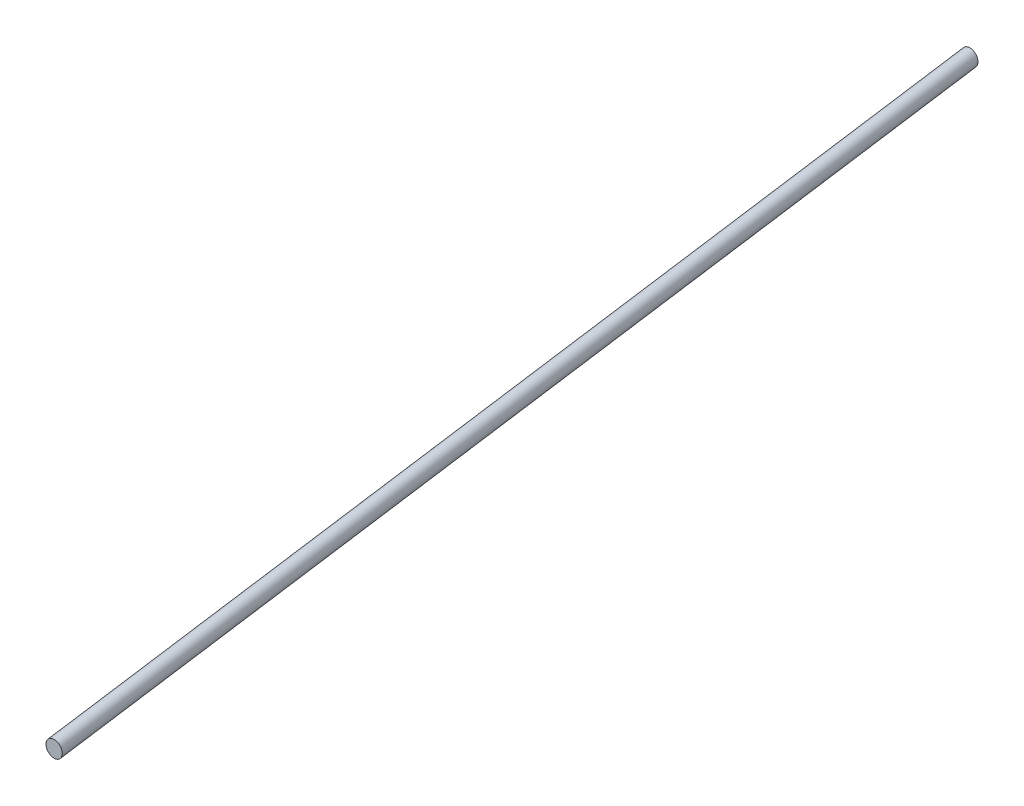
SolidWorks part; units mm, degrees
ref_plane "前视基准面" through (0, 0, 0) normal (0, 0, 1) x (1, 0, 0)
ref_plane "上视基准面" through (0, 0, 0) normal (0, 1, 0) x (1, 0, 0)
ref_plane "右视基准面" through (0, 0, 0) normal (1, 0, 0) x (0, 0, -1)
curve "曲线1"
  spline degree 3 poles (186.5, 0.1118, 0) (186.1892, 0.1855, 0) (185.5675, 0.3328, 0) (184.635, 0.5537, 0) (183.7026, 0.7744, 0) (182.7701, 0.9948, 0) (181.8376, 1.2145, 0) (180.9051, 1.4337, 0) (179.9726, 1.652, 0) (178.7297, 1.9419, 0) (177.1757, 2.3014, 0) (175.3109, 2.728, 0) (173.4457, 3.1494, 0) (171.5809, 3.5657, 0) (169.7157, 3.9772, 0) (167.8508, 4.3838, 0) (165.9856, 4.7859, 0) (164.1208, 5.1833, 0) (162.2556, 5.576, 0) (160.3908, 5.9638, 0) (158.5257, 6.3468, 0) (156.6608, 6.7247, 0) (154.7957, 7.0976, 0) (152.9308, 7.4653, 0) (151.0657, 7.8278, 0) (149.2008, 8.185, 0) (147.3357, 8.5369, 0) (145.4708, 8.8834, 0) (143.6056, 9.2245, 0) (141.7408, 9.5601, 0) (139.8756, 9.8903, 0) (138.0108, 10.2149, 0) (136.1456, 10.5341, 0) (134.2808, 10.8476, 0) (132.4156, 11.1557, 0) (130.5507, 11.4581, 0) (128.6856, 11.7549, 0) (126.8208, 12.0459, 0) (124.9556, 12.3308, 0) (123.0908, 12.6092, 0) (121.2257, 12.8811, 0) (119.3608, 13.146, 0) (117.4957, 13.4038, 0) (115.6308, 13.654, 0) (113.7657, 13.8966, 0) (111.9008, 14.1311, 0) (110.0357, 14.3574, 0) (108.1708, 14.5754, 0) (106.3056, 14.785, 0) (104.4407, 14.9862, 0) (102.5756, 15.1791, 0) (100.7107, 15.3636, 0) (98.8455, 15.5397, 0) (96.9806, 15.7073, 0) (95.1155, 15.8666, 0) (93.2506, 16.0175, 0) (91.3854, 16.1599, 0) (89.5205, 16.2936, 0) (87.6554, 16.4183, 0) (85.7905, 16.5335, 0) (83.9254, 16.6389, 0) (82.0604, 16.734, 0) (80.1953, 16.8187, 0) (78.3303, 16.8924, 0) (76.4652, 16.9548, 0) (74.6002, 17.0055, 0) (72.7351, 17.0439, 0) (70.8701, 17.0706, 0) (69.005, 17.0858, 0) (67.14, 17.0901, 0) (65.275, 17.0839, 0) (63.4099, 17.0678, 0) (61.5449, 17.0422, 0) (59.6799, 17.0076, 0) (57.8149, 16.9643, 0) (55.9498, 16.9131, 0) (54.0848, 16.8547, 0) (52.2196, 16.7871, 0) (50.3546, 16.7086, 0) (48.4893, 16.6167, 0) (46.6243, 16.5092, 0) (44.7588, 16.3837, 0) (42.8937, 16.238, 0) (41.028, 16.0697, 0) (39.163, 15.8765, 0) (37.2969, 15.6558, 0) (35.4322, 15.405, 0) (33.5661, 15.1238, 0) (31.7016, 14.8124, 0) (29.8355, 14.4709, 0) (27.971, 14.1006, 0) (26.1044, 13.6997, 0) (24.2398, 13.2683, 0) (22.3723, 12.8019, 0) (20.5078, 12.299, 0) (18.6397, 11.7536, 0) (16.7761, 11.1641, 0) (14.9067, 10.5272, 0) (13.0406, 9.8463, 0) (11.4871, 9.2257, 0) (10.251, 8.6897, 0) (9.3149, 8.2577, 0) (8.3827, 7.7965, 0) (7.4442, 7.2957, 0) (6.5109, 6.7553, 0) (5.5667, 6.1517, 0) (4.6345, 5.4819, 0) (3.7611, 4.7729, 0) (2.9674, 4.0489, 0) (2.3522, 3.4464, 0) (1.8596, 2.9514, 0) (1.4788, 2.552, 0) (1.1014, 2.1276, 0) (0.7887, 1.7312, 0) (0.5474, 1.381, 0) (0.3916, 1.1217, 0) (0.2725, 0.8921, 0) (0.1949, 0.7195, 0) (0.136, 0.5671, 0) (0.0831, 0.4095, 0) (0.0327, 0.2211, 0) (-0.0162, -0.071, 0) (-0.0149, -0.4421, 0) (0.0563, -0.7734, 0) (0.1356, -0.9912, 0) (0.1948, -1.1301, 0) (0.2723, -1.2864, 0) (0.3907, -1.4912, 0) (0.546, -1.7187, 0) (0.7851, -2.0147, 0) (1.0965, -2.3364, 0) (1.4716, -2.656, 0) (1.8524, -2.9339, 0) (2.3365, -3.2337, 0) (2.9612, -3.5284, 0) (3.7741, -3.807, 0) (4.6559, -4.0277, 0) (5.5923, -4.2156, 0) (6.5261, -4.402, 0) (7.4574, -4.5763, 0) (8.3903, -4.7294, 0) (9.3228, -4.8608, 0) (10.2562, -4.9705, 0) (11.4987, -5.092, 0) (13.0535, -5.2066, 0) (14.9192, -5.3092, 0) (16.7846, -5.4024, 0) (18.6495, -5.482, 0) (20.5147, -5.5442, 0) (22.3797, -5.5905, 0) (24.2449, -5.6228, 0) (26.1099, -5.6419, 0) (27.975, -5.6487, 0) (29.84, -5.6442, 0) (31.7051, -5.6295, 0) (33.5701, -5.6055, 0) (35.4351, -5.5733, 0) (37.3001, -5.5337, 0) (39.1651, -5.4878, 0) (41.0301, -5.4363, 0) (42.8951, -5.3798, 0) (44.7601, -5.3192, 0) (46.6251, -5.2551, 0) (48.4901, -5.1881, 0) (50.355, -5.1191, 0) (52.22, -5.0486, 0) (54.085, -4.9774, 0) (55.95, -4.9063, 0) (57.815, -4.8359, 0) (59.68, -4.7662, 0) (61.545, -4.6971, 0) (63.41, -4.6284, 0) (65.275, -4.5602, 0) (67.14, -4.4922, 0) (69.005, -4.4244, 0) (70.87, -4.3567, 0) (72.735, -4.2891, 0) (74.6, -4.2213, 0) (76.465, -4.1533, 0) (78.33, -4.0852, 0) (80.195, -4.0168, 0) (82.06, -3.9484, 0) (83.925, -3.8798, 0) (85.79, -3.8112, 0) (87.655, -3.7425, 0) (89.52, -3.6738, 0) (91.385, -3.6051, 0) (93.25, -3.5364, 0) (95.115, -3.4678, 0) (96.98, -3.3992, 0) (98.845, -3.3306, 0) (100.71, -3.2621, 0) (102.575, -3.1937, 0) (104.44, -3.1252, 0) (106.305, -3.0568, 0) (108.17, -2.9883, 0) (110.035, -2.9199, 0) (111.9, -2.8515, 0) (113.765, -2.783, 0) (115.63, -2.7145, 0) (117.495, -2.6461, 0) (119.36, -2.5776, 0) (121.225, -2.5091, 0) (123.09, -2.4406, 0) (124.955, -2.3721, 0) (126.82, -2.3035, 0) (128.685, -2.2351, 0) (130.55, -2.1665, 0) (132.415, -2.0981, 0) (134.28, -2.0295, 0) (136.145, -1.9611, 0) (138.01, -1.8926, 0) (139.875, -1.8241, 0) (141.74, -1.7556, 0) (143.605, -1.6871, 0) (145.47, -1.6186, 0) (147.335, -1.5501, 0) (149.2, -1.4816, 0) (151.065, -1.4131, 0) (152.93, -1.3446, 0) (154.795, -1.2761, 0) (156.66, -1.2076, 0) (158.525, -1.1392, 0) (160.39, -1.0707, 0) (162.255, -1.0022, 0) (164.12, -0.9337, 0) (165.985, -0.8652, 0) (167.85, -0.7967, 0) (169.715, -0.7282, 0) (171.58, -0.6597, 0) (173.445, -0.5912, 0) (175.31, -0.5227, 0) (177.175, -0.4542, 0) (178.7292, -0.3972, 0) (179.9725, -0.3515, 0) (180.905, -0.3173, 0) (181.8375, -0.283, 0) (182.77, -0.2488, 0) (183.7025, -0.2145, 0) (184.635, -0.1803, 0) (185.5675, -0.146, 0) (186.1892, -0.1232, 0) (186.5, -0.1118, 0) knots 0 0 0 0 0.002514 0.005028 0.007541 0.010055 0.012567 0.01508 0.017592 0.020104 0.025124 0.030144 0.035158 0.040172 0.04518 0.050189 0.055192 0.060195 0.065193 0.070191 0.075184 0.080177 0.085164 0.090152 0.095134 0.100117 0.105094 0.110071 0.115043 0.120015 0.124982 0.129949 0.134911 0.139873 0.14483 0.149787 0.154739 0.159692 0.164639 0.169587 0.174529 0.179472 0.184409 0.189346 0.194278 0.19921 0.204137 0.209064 0.213985 0.218907 0.223824 0.228741 0.233654 0.238567 0.243476 0.248385 0.25329 0.258196 0.263098 0.268 0.2729 0.277799 0.282695 0.287592 0.292486 0.29738 0.302273 0.307166 0.312058 0.316951 0.321843 0.326735 0.331628 0.33652 0.341414 0.346308 0.351203 0.356098 0.360995 0.365892 0.370794 0.375696 0.380605 0.385515 0.390437 0.39536 0.400301 0.405243 0.410209 0.415176 0.420172 0.425167 0.430199 0.435232 0.440314 0.445396 0.450545 0.455694 0.460935 0.466175 0.468856 0.471537 0.474288 0.477039 0.479906 0.482773 0.485854 0.488934 0.491619 0.494305 0.49571 0.497115 0.498647 0.500178 0.501085 0.501992 0.502556 0.503119 0.50348 0.503841 0.504427 0.505013 0.506168 0.507324 0.507658 0.507992 0.508511 0.50903 0.509853 0.510676 0.512022 0.513369 0.514549 0.515728 0.517845 0.519968 0.522481 0.524993 0.527484 0.529974 0.532448 0.534923 0.537383 0.539844 0.544747 0.54965 0.554547 0.559445 0.564339 0.569233 0.574126 0.579018 0.58391 0.588803 0.593695 0.598587 0.60348 0.608373 0.613267 0.618161 0.623055 0.62795 0.632845 0.63774 0.642636 0.647531 0.652427 0.657322 0.662218 0.667113 0.672009 0.676904 0.6818 0.686695 0.69159 0.696486 0.701381 0.706276 0.711172 0.716067 0.720962 0.725858 0.730753 0.735649 0.740544 0.745439 0.750335 0.75523 0.760126 0.765021 0.769916 0.774812 0.779707 0.784603 0.789498 0.794393 0.799289 0.804184 0.80908 0.813975 0.81887 0.823766 0.828661 0.833557 0.838452 0.843347 0.848243 0.853138 0.858034 0.862929 0.867824 0.87272 0.877615 0.882511 0.887406 0.892301 0.897197 0.902092 0.906987 0.911883 0.916778 0.921674 0.926569 0.931464 0.93636 0.941255 0.946151 0.951046 0.955941 0.960837 0.965732 0.970628 0.975523 0.980418 0.982866 0.985314 0.987762 0.990209 0.992657 0.995105 0.997552 1 1 1 1
sketch "草图1" plane through (0, 0, 0) normal (0, 0, 1) x (1, 0, 0)
  line L0 (186.5, 0.1118) -> (187.3165, -0.0818)
  line L1 (186.5, -0.1118) -> (187.3165, -0.0818)
  spline S0 degree 3 poles (1071.8943, 1773.6481) (478.7543, -73.3687) (332.3255, -34.4387) (184.635, 0.5537) (183.7026, 0.7744) (182.7701, 0.9948) (181.8376, 1.2145) (180.9051, 1.4337) (179.9726, 1.652) (178.7297, 1.9419) (177.1757, 2.3014) (175.3109, 2.728) (173.4457, 3.1494) (170.9597, 3.7043) (167.8519, 4.3859) (164.1219, 5.1854) (159.7716, 6.0959) (156.0406, 6.8521) (152.9308, 7.4653) (151.0657, 7.8278) (149.2008, 8.185) (147.3357, 8.5369) (145.4708, 8.8834) (143.6056, 9.2245) (141.7408, 9.5601) (139.2547, 10.0002) (136.7681, 10.4294) (134.2808, 10.8476) (132.4156, 11.1557) (130.5507, 11.4581) (128.6856, 11.7549) (126.8208, 12.0459) (124.9556, 12.3308) (123.0908, 12.6092) (121.2257, 12.8811) (119.3608, 13.146) (117.4957, 13.4038) (115.0097, 13.7374) (112.523, 14.0557) (109.4148, 14.4328) (106.9281, 14.7178) (104.4407, 14.9862) (102.5756, 15.1791) (100.7107, 15.3636) (98.8455, 15.5397) (96.3593, 15.7632) (93.2513, 16.0216) (90.1425, 16.252) (87.6554, 16.4183) (85.7905, 16.5335) (83.9254, 16.6389) (82.0604, 16.734) (80.1953, 16.8187) (78.3303, 16.8924) (76.4652, 16.9548) (73.9787, 17.0223) (71.4919, 17.0655) (69.005, 17.0858) (67.14, 17.0901) (65.275, 17.0839) (63.4099, 17.0678) (61.5449, 17.0422) (59.6799, 17.0076) (57.8149, 16.9643) (55.9498, 16.9131) (54.0848, 16.8547) (52.2196, 16.7871) (50.3546, 16.7086) (48.4893, 16.6167) (46.6243, 16.5092) (44.7588, 16.3837) (42.8937, 16.238) (41.028, 16.0697) (39.163, 15.8765) (37.2969, 15.6558) (35.4322, 15.405) (33.5661, 15.1238) (31.7016, 14.8124) (29.8355, 14.4709) (27.971, 14.1006) (26.1044, 13.6997) (24.2398, 13.2683) (22.3723, 12.8019) (20.5078, 12.299) (18.6397, 11.7536) (16.7761, 11.1641) (14.9067, 10.5272) (13.0406, 9.8463) (11.4871, 9.2257) (10.251, 8.6897) (9.3149, 8.2577) (8.3827, 7.7965) (7.4442, 7.2957) (6.5109, 6.7553) (5.5667, 6.1517) (4.6345, 5.4819) (3.7611, 4.7729) (2.9674, 4.0489) (2.3522, 3.4464) (1.8596, 2.9514) (1.4788, 2.552) (1.1014, 2.1276) (0.7887, 1.7312) (0.5474, 1.381) (0.3916, 1.1217) (0.2725, 0.8921) (0.1949, 0.7195) (0.136, 0.5671) (0.0831, 0.4095) (0.0327, 0.2211) (-0.0162, -0.071) (-0.0149, -0.4421) (0.0563, -0.7734) (0.1356, -0.9912) (0.1948, -1.1301) (0.2723, -1.2864) (0.3907, -1.4912) (0.546, -1.7187) (0.7851, -2.0147) (1.0965, -2.3364) (1.4716, -2.656) (1.8524, -2.9339) (2.3365, -3.2337) (2.9612, -3.5284) (3.7741, -3.807) (4.6559, -4.0277) (5.5923, -4.2156) (6.5261, -4.402) (7.4574, -4.5763) (8.3903, -4.7294) (9.3228, -4.8608) (10.2562, -4.9705) (11.4987, -5.092) (13.0535, -5.2066) (14.9192, -5.3092) (16.7846, -5.4024) (18.6495, -5.482) (20.5147, -5.5442) (22.3797, -5.5905) (24.8665, -5.6336) (27.3533, -5.6502) (29.84, -5.6442) (32.3268, -5.6246) (34.8135, -5.5864) (37.3001, -5.5337) (39.1651, -5.4878) (42.2737, -5.4019) (45.3819, -5.2997) (49.1118, -5.1658) (51.5984, -5.0723) (54.085, -4.9774) (57.1933, -4.8589) (61.5449, -4.6964) (66.5183, -4.5147) (70.2483, -4.3793) (73.3567, -4.2665) (75.8433, -4.176) (78.33, -4.0852) (80.195, -4.0168) (82.06, -3.9484) (83.925, -3.8798) (85.79, -3.8112) (87.655, -3.7425) (89.52, -3.6738) (91.385, -3.6051) (93.25, -3.5364) (95.7367, -3.4449) (98.2233, -3.3535) (100.71, -3.2621) (102.575, -3.1937) (104.44, -3.1252) (106.305, -3.0568) (108.7917, -2.9655) (111.2783, -2.8743) (113.765, -2.783) (116.8733, -2.6689) (119.9817, -2.5547) (123.09, -2.4406) (124.955, -2.3721) (126.82, -2.3035) (129.3067, -2.2122) (131.7933, -2.1209) (134.28, -2.0295) (136.145, -1.9611) (138.01, -1.8926) (140.4967, -1.8012) (142.9833, -1.7099) (145.47, -1.6186) (147.335, -1.5501) (149.8217, -1.4588) (152.3083, -1.3675) (154.795, -1.2761) (156.66, -1.2076) (158.525, -1.1392) (160.39, -1.0707) (162.255, -1.0022) (164.12, -0.9337) (166.6067, -0.8424) (169.0933, -0.751) (171.58, -0.6597) (174.0667, -0.5684) (176.5533, -0.4771) (179.04, -0.3857) (180.5942, -0.3287) (182.1483, -0.2716) (183.3917, -0.2259) (184.635, -0.1803) (849.3977, 24.2359) (1513.8472, 48.7041) (2182.9555, -62.1484) knots -1.186859 -1.186859 -1.186859 -1.186859 0.002514 0.005028 0.007541 0.010055 0.012567 0.01508 0.017592 0.020104 0.025124 0.030144 0.035158 0.040172 0.050189 0.060195 0.070191 0.085164 0.090152 0.095134 0.100117 0.105094 0.110071 0.115043 0.120015 0.124982 0.134911 0.139873 0.14483 0.149787 0.154739 0.159692 0.164639 0.169587 0.174529 0.179472 0.184409 0.189346 0.19921 0.204137 0.213985 0.218907 0.223824 0.228741 0.233654 0.238567 0.248385 0.258196 0.263098 0.268 0.2729 0.277799 0.282695 0.287592 0.292486 0.29738 0.307166 0.312058 0.316951 0.321843 0.326735 0.331628 0.33652 0.341414 0.346308 0.351203 0.356098 0.360995 0.365892 0.370794 0.375696 0.380605 0.385515 0.390437 0.39536 0.400301 0.405243 0.410209 0.415176 0.420172 0.425167 0.430199 0.435232 0.440314 0.445396 0.450545 0.455694 0.460935 0.466175 0.468856 0.471537 0.474288 0.477039 0.479906 0.482773 0.485854 0.488934 0.491619 0.494305 0.49571 0.497115 0.498647 0.500178 0.501085 0.501992 0.502556 0.503119 0.50348 0.503841 0.504427 0.505013 0.506168 0.507324 0.507658 0.507992 0.508511 0.50903 0.509853 0.510676 0.512022 0.513369 0.514549 0.515728 0.517845 0.519968 0.522481 0.524993 0.527484 0.529974 0.532448 0.534923 0.537383 0.539844 0.544747 0.54965 0.554547 0.559445 0.564339 0.569233 0.574126 0.58391 0.588803 0.593695 0.60348 0.608373 0.613267 0.618161 0.632845 0.63774 0.647531 0.652427 0.657322 0.672009 0.686695 0.696486 0.701381 0.711172 0.716067 0.720962 0.725858 0.730753 0.735649 0.740544 0.745439 0.750335 0.75523 0.760126 0.769916 0.774812 0.779707 0.784603 0.789498 0.794393 0.804184 0.80908 0.813975 0.828661 0.833557 0.838452 0.843347 0.848243 0.858034 0.862929 0.867824 0.87272 0.877615 0.887406 0.892301 0.897197 0.902092 0.911883 0.916778 0.921674 0.926569 0.931464 0.93636 0.941255 0.946151 0.955941 0.960837 0.965732 0.975523 0.980418 0.985314 0.987762 0.992657 0.995105 0.997552 6.227418 6.227418 6.227418 6.227418 only from (186.5, 0.1118) to (186.5, -0.1118) construction
  spline S1 degree 3 poles (186.5, 0.1118) (185.8783, 0.2591) (184.9459, 0.4802) (183.7026, 0.7744) (182.7701, 0.9948) (181.8376, 1.2145) (180.9051, 1.4337) (179.9726, 1.652) (178.7297, 1.9419) (177.1757, 2.3014) (175.3109, 2.728) (173.4457, 3.1494) (170.9597, 3.7043) (167.8519, 4.3859) (164.1219, 5.1854) (159.7716, 6.0959) (156.0406, 6.8521) (152.9308, 7.4653) (151.0657, 7.8278) (149.2008, 8.185) (147.3357, 8.5369) (145.4708, 8.8834) (143.6056, 9.2245) (141.7408, 9.5601) (139.2547, 10.0002) (136.7681, 10.4294) (134.2808, 10.8476) (132.4156, 11.1557) (130.5507, 11.4581) (128.6856, 11.7549) (126.8208, 12.0459) (124.9556, 12.3308) (123.0908, 12.6092) (121.2257, 12.8811) (119.3608, 13.146) (117.4957, 13.4038) (115.0097, 13.7374) (112.523, 14.0557) (109.4148, 14.4328) (106.9281, 14.7178) (104.4407, 14.9862) (102.5756, 15.1791) (100.7107, 15.3636) (98.8455, 15.5397) (96.3593, 15.7632) (93.2513, 16.0216) (90.1425, 16.252) (87.6554, 16.4183) (85.7905, 16.5335) (83.9254, 16.6389) (82.0604, 16.734) (80.1953, 16.8187) (78.3303, 16.8924) (76.4652, 16.9548) (73.9787, 17.0223) (71.4919, 17.0655) (69.005, 17.0858) (67.14, 17.0901) (65.275, 17.0839) (63.4099, 17.0678) (61.5449, 17.0422) (59.6799, 17.0076) (57.8149, 16.9643) (55.9498, 16.9131) (54.0848, 16.8547) (52.2196, 16.7871) (50.3546, 16.7086) (48.4893, 16.6167) (46.6243, 16.5092) (44.7588, 16.3837) (42.8937, 16.238) (41.028, 16.0697) (39.163, 15.8765) (37.2969, 15.6558) (35.4322, 15.405) (33.5661, 15.1238) (31.7016, 14.8124) (29.8355, 14.4709) (27.971, 14.1006) (26.1044, 13.6997) (24.2398, 13.2683) (22.3723, 12.8019) (20.5078, 12.299) (18.6397, 11.7536) (16.7761, 11.1641) (14.9067, 10.5272) (13.0406, 9.8463) (11.4871, 9.2257) (10.251, 8.6897) (9.3149, 8.2577) (8.3827, 7.7965) (7.4442, 7.2957) (6.5109, 6.7553) (5.5667, 6.1517) (4.6345, 5.4819) (3.7611, 4.7729) (2.9674, 4.0489) (2.3522, 3.4464) (1.8596, 2.9514) (1.4788, 2.552) (1.1014, 2.1276) (0.7887, 1.7312) (0.5474, 1.381) (0.3916, 1.1217) (0.2725, 0.8921) (0.1949, 0.7195) (0.136, 0.5671) (0.0831, 0.4095) (0.0327, 0.2211) (-0.0162, -0.071) (-0.0149, -0.4421) (0.0563, -0.7734) (0.1356, -0.9912) (0.1948, -1.1301) (0.2723, -1.2864) (0.3907, -1.4912) (0.546, -1.7187) (0.7851, -2.0147) (1.0965, -2.3364) (1.4716, -2.656) (1.8524, -2.9339) (2.3365, -3.2337) (2.9612, -3.5284) (3.7741, -3.807) (4.6559, -4.0277) (5.5923, -4.2156) (6.5261, -4.402) (7.4574, -4.5763) (8.3903, -4.7294) (9.3228, -4.8608) (10.2562, -4.9705) (11.4987, -5.092) (13.0535, -5.2066) (14.9192, -5.3092) (16.7846, -5.4024) (18.6495, -5.482) (20.5147, -5.5442) (22.3797, -5.5905) (24.8665, -5.6336) (27.3533, -5.6502) (29.84, -5.6442) (32.3268, -5.6246) (34.8135, -5.5864) (37.3001, -5.5337) (39.1651, -5.4878) (42.2737, -5.4019) (45.3819, -5.2997) (49.1118, -5.1658) (51.5984, -5.0723) (54.085, -4.9774) (57.1933, -4.8589) (61.5449, -4.6964) (66.5183, -4.5147) (70.2483, -4.3793) (73.3567, -4.2665) (75.8433, -4.176) (78.33, -4.0852) (80.195, -4.0168) (82.06, -3.9484) (83.925, -3.8798) (85.79, -3.8112) (87.655, -3.7425) (89.52, -3.6738) (91.385, -3.6051) (93.25, -3.5364) (95.7367, -3.4449) (98.2233, -3.3535) (100.71, -3.2621) (102.575, -3.1937) (104.44, -3.1252) (106.305, -3.0568) (108.7917, -2.9655) (111.2783, -2.8743) (113.765, -2.783) (116.8733, -2.6689) (119.9817, -2.5547) (123.09, -2.4406) (124.955, -2.3721) (126.82, -2.3035) (129.3067, -2.2122) (131.7933, -2.1209) (134.28, -2.0295) (136.145, -1.9611) (138.01, -1.8926) (140.4967, -1.8012) (142.9833, -1.7099) (145.47, -1.6186) (147.335, -1.5501) (149.8217, -1.4588) (152.3083, -1.3675) (154.795, -1.2761) (156.66, -1.2076) (158.525, -1.1392) (160.39, -1.0707) (162.255, -1.0022) (164.12, -0.9337) (166.6067, -0.8424) (169.0933, -0.751) (171.58, -0.6597) (174.0667, -0.5684) (176.5533, -0.4771) (179.04, -0.3857) (180.5942, -0.3287) (182.1483, -0.2716) (184.0133, -0.2031) (185.5675, -0.146) (186.5, -0.1118) knots 0 0 0 0 0.005028 0.007541 0.010055 0.012567 0.01508 0.017592 0.020104 0.025124 0.030144 0.035158 0.040172 0.050189 0.060195 0.070191 0.085164 0.090152 0.095134 0.100117 0.105094 0.110071 0.115043 0.120015 0.124982 0.134911 0.139873 0.14483 0.149787 0.154739 0.159692 0.164639 0.169587 0.174529 0.179472 0.184409 0.189346 0.19921 0.204137 0.213985 0.218907 0.223824 0.228741 0.233654 0.238567 0.248385 0.258196 0.263098 0.268 0.2729 0.277799 0.282695 0.287592 0.292486 0.29738 0.307166 0.312058 0.316951 0.321843 0.326735 0.331628 0.33652 0.341414 0.346308 0.351203 0.356098 0.360995 0.365892 0.370794 0.375696 0.380605 0.385515 0.390437 0.39536 0.400301 0.405243 0.410209 0.415176 0.420172 0.425167 0.430199 0.435232 0.440314 0.445396 0.450545 0.455694 0.460935 0.466175 0.468856 0.471537 0.474288 0.477039 0.479906 0.482773 0.485854 0.488934 0.491619 0.494305 0.49571 0.497115 0.498647 0.500178 0.501085 0.501992 0.502556 0.503119 0.50348 0.503841 0.504427 0.505013 0.506168 0.507324 0.507658 0.507992 0.508511 0.50903 0.509853 0.510676 0.512022 0.513369 0.514549 0.515728 0.517845 0.519968 0.522481 0.524993 0.527484 0.529974 0.532448 0.534923 0.537383 0.539844 0.544747 0.54965 0.554547 0.559445 0.564339 0.569233 0.574126 0.58391 0.588803 0.593695 0.60348 0.608373 0.613267 0.618161 0.632845 0.63774 0.647531 0.652427 0.657322 0.672009 0.686695 0.696486 0.701381 0.711172 0.716067 0.720962 0.725858 0.730753 0.735649 0.740544 0.745439 0.750335 0.75523 0.760126 0.769916 0.774812 0.779707 0.784603 0.789498 0.794393 0.804184 0.80908 0.813975 0.828661 0.833557 0.838452 0.843347 0.848243 0.858034 0.862929 0.867824 0.87272 0.877615 0.887406 0.892301 0.897197 0.902092 0.911883 0.916778 0.921674 0.926569 0.931464 0.93636 0.941255 0.946151 0.955941 0.960837 0.965732 0.975523 0.980418 0.985314 0.987762 0.992657 1 1 1 1
curve "组合曲线1"
ref_plane "基准面4" through (0, 0, 519) normal (0, 0, 1) x (1, 0, 0)
sketch "草图2" plane through (0, 0, 519) normal (0, 0, 1) x (1, 0, 0)
  line L2 (187.3165, -0.0818) -> (186.8021, 0.0402)
  line L3 (186.8021, -0.1007) -> (187.3165, -0.0818)
  spline S1 degree 3 poles (186.8021, 0.0402) (186.2146, 0.1794) (185.4313, 0.3651) (184.4521, 0.5965) (183.8645, 0.735) (183.2771, 0.873) (182.6895, 1.0106) (181.9064, 1.1932) (180.9273, 1.4197) (179.7524, 1.6885) (178.5773, 1.954) (177.011, 2.3036) (175.0529, 2.733) (172.7029, 3.2368) (169.962, 3.8104) (167.6113, 4.2869) (165.652, 4.6732) (164.0857, 4.9777) (162.519, 5.2755) (160.9518, 5.5667) (159.7767, 5.7816) (158.6017, 5.993) (157.0354, 6.2703) (155.4687, 6.5408) (153.9016, 6.8042) (152.7265, 6.9983) (151.5515, 7.1888) (150.3764, 7.3759) (149.2015, 7.5592) (148.0263, 7.7387) (146.8514, 7.9141) (145.2851, 8.1425) (143.7184, 8.3621) (141.7599, 8.6249) (140.1932, 8.8254) (138.2349, 9.063) (136.6682, 9.2426) (135.101, 9.4117) (133.9259, 9.5333) (132.7509, 9.6495) (131.5758, 9.7604) (130.0094, 9.9013) (128.0512, 10.0641) (126.0925, 10.2092) (124.5255, 10.314) (123.3505, 10.3866) (122.1754, 10.453) (121.0004, 10.5129) (119.8253, 10.5663) (118.6503, 10.6127) (117.4752, 10.652) (115.9086, 10.6946) (114.3418, 10.7218) (112.775, 10.7346) (111.5999, 10.7373) (110.4248, 10.7334) (109.2498, 10.7232) (108.0747, 10.7071) (106.8997, 10.6853) (105.7246, 10.658) (104.5496, 10.6257) (103.3745, 10.5889) (102.1994, 10.5464) (101.0243, 10.4969) (99.8491, 10.439) (98.6741, 10.3713) (97.4987, 10.2922) (96.3237, 10.2004) (95.1481, 10.0944) (93.9731, 9.9727) (92.7974, 9.8336) (91.6225, 9.6756) (90.4468, 9.4984) (89.2721, 9.3022) (88.0964, 9.0871) (86.9217, 8.8538) (85.7456, 8.6012) (84.5708, 8.3294) (83.3943, 8.0355) (82.2195, 7.7187) (81.0425, 7.375) (79.8683, 7.0036) (78.6906, 6.6023) (77.5148, 6.1733) (76.5361, 5.7823) (75.7573, 5.4447) (75.1675, 5.1725) (74.5801, 4.8819) (73.9888, 4.5664) (73.4008, 4.2259) (72.806, 3.8456) (72.2186, 3.4236) (71.6683, 2.9769) (71.1683, 2.5208) (70.7807, 2.1411) (70.4703, 1.8292) (70.2304, 1.5776) (69.9926, 1.3102) (69.7956, 1.0605) (69.6436, 0.8398) (69.5454, 0.6765) (69.4703, 0.5318) (69.4215, 0.4231) (69.3844, 0.327) (69.3511, 0.2278) (69.3193, 0.1091) (69.2885, -0.075) (69.2893, -0.3088) (69.3342, -0.5175) (69.3841, -0.6548) (69.4214, -0.7423) (69.4702, -0.8408) (69.5448, -0.9698) (69.6427, -1.1131) (69.7933, -1.2996) (69.9895, -1.5023) (70.2258, -1.7037) (70.4657, -1.8787) (70.7708, -2.0676) (71.1644, -2.2533) (71.6765, -2.4288) (72.2321, -2.5679) (72.8221, -2.6862) (73.4104, -2.8037) (73.9972, -2.9135) (74.585, -3.01) (75.1724, -3.0928) (75.7605, -3.1619) (76.5434, -3.2385) (77.5229, -3.3106) (78.6984, -3.3753) (79.8737, -3.434) (81.0487, -3.4842) (82.2238, -3.5233) (83.3989, -3.5525) (84.9657, -3.5796) (86.5325, -3.5901) (88.0992, -3.5863) (89.666, -3.574) (91.2328, -3.55) (92.7994, -3.5167) (93.9744, -3.4878) (95.933, -3.4337) (97.8913, -3.3693) (100.2413, -3.2849) (102.1997, -3.2113) (104.9413, -3.1062) (108.0747, -2.9892) (111.2082, -2.8747) (113.5583, -2.7894) (115.5167, -2.7184) (117.0834, -2.6614) (118.6501, -2.6041) (119.8251, -2.561) (121.0002, -2.5179) (122.1752, -2.4747) (123.7419, -2.4171) (125.3086, -2.3593) (126.8753, -2.3016) (128.0504, -2.2583) (129.6171, -2.2007) (131.1838, -2.1431) (132.7505, -2.0856) (133.9255, -2.0424) (135.1006, -1.9993) (136.2756, -1.9562) (137.8423, -1.8987) (139.409, -1.8412) (140.9757, -1.7837) (142.9341, -1.7118) (144.8925, -1.6398) (147.2426, -1.5536) (148.8093, -1.496) (150.7677, -1.4241) (152.3344, -1.3665) (153.9011, -1.309) (155.0761, -1.2658) (156.2512, -1.2227) (157.8179, -1.1651) (159.3846, -1.1076) (160.9513, -1.05) (162.1264, -1.0069) (163.6931, -0.9494) (165.2598, -0.8918) (166.8265, -0.8343) (168.7849, -0.7623) (170.7433, -0.6904) (172.7017, -0.6185) (174.2684, -0.561) (175.8351, -0.5034) (177.4018, -0.4459) (178.9685, -0.3884) (180.5352, -0.3308) (182.1019, -0.2733) (183.0811, -0.2373) (184.0603, -0.2014) (185.2354, -0.1582) (186.2145, -0.1223) (186.8021, -0.1007) knots 0 0 0 0 0.007541 0.010055 0.012567 0.01508 0.017592 0.020104 0.025124 0.030144 0.035158 0.040172 0.050189 0.060195 0.070191 0.085164 0.090152 0.095134 0.105094 0.110071 0.115043 0.120015 0.124982 0.134911 0.139873 0.14483 0.149787 0.154739 0.159692 0.164639 0.169587 0.174529 0.184409 0.189346 0.19921 0.204137 0.213985 0.218907 0.223824 0.228741 0.233654 0.238567 0.248385 0.258196 0.263098 0.268 0.2729 0.277799 0.282695 0.287592 0.292486 0.29738 0.307166 0.312058 0.316951 0.321843 0.326735 0.331628 0.33652 0.341414 0.346308 0.351203 0.356098 0.360995 0.365892 0.370794 0.375696 0.380605 0.385515 0.390437 0.39536 0.400301 0.405243 0.410209 0.415176 0.420172 0.425167 0.430199 0.435232 0.440314 0.445396 0.450545 0.455694 0.460935 0.466175 0.468856 0.471537 0.474288 0.477039 0.479906 0.482773 0.485854 0.488934 0.491619 0.494305 0.49571 0.497115 0.498647 0.500178 0.501085 0.501992 0.502556 0.503119 0.50348 0.503841 0.504427 0.505013 0.506168 0.507324 0.507658 0.507992 0.508511 0.50903 0.509853 0.510676 0.512022 0.513369 0.514549 0.515728 0.517845 0.519968 0.522481 0.524993 0.527484 0.529974 0.532448 0.534923 0.537383 0.539844 0.544747 0.54965 0.554547 0.559445 0.564339 0.569233 0.574126 0.58391 0.588803 0.593695 0.60348 0.608373 0.613267 0.618161 0.632845 0.63774 0.647531 0.657322 0.672009 0.686695 0.696486 0.701381 0.711172 0.716067 0.720962 0.725858 0.730753 0.735649 0.745439 0.750335 0.75523 0.760126 0.769916 0.774812 0.779707 0.784603 0.789498 0.794393 0.804184 0.80908 0.813975 0.828661 0.833557 0.843347 0.848243 0.858034 0.862929 0.867824 0.87272 0.877615 0.887406 0.892301 0.897197 0.902092 0.911883 0.916778 0.921674 0.93636 0.941255 0.946151 0.955941 0.960837 0.965732 0.975523 0.980418 0.985314 0.987762 0.992657 1 1 1 1
curve "组合曲线2"
sketch3d "3D草图1"
  line L0 (-0.0101, -0.1358, 0) -> (69.2923, -0.1173, 519)
  line L1 (187.3165, -0.0818, 0) -> (187.3165, -0.0818, 519)
  line L2 (187.3165, -0.0818, 0) -> (186.5, 0.1118, 0) construction
  line L3 (186.5, -0.1118, 0) -> (187.3165, -0.0818, 0) construction
  line L4 (187.3165, -0.0818, 519) -> (186.8021, 0.0402, 519) construction
  line L5 (186.8021, -0.1007, 519) -> (187.3165, -0.0818, 519) construction
  spline S0 degree 3 poles (186.5, 0.1118, 0) (185.8783, 0.2591, 0) (184.9459, 0.4802, 0) (183.7026, 0.7744, 0) (182.7701, 0.9948, 0) (181.8376, 1.2145, 0) (180.9051, 1.4337, 0) (179.9726, 1.652, 0) (178.7297, 1.9419, 0) (177.1757, 2.3014, 0) (175.3109, 2.728, 0) (173.4457, 3.1494, 0) (170.9597, 3.7043, 0) (167.8519, 4.3859, 0) (164.1219, 5.1854, 0) (159.7716, 6.0959, 0) (156.0406, 6.8521, 0) (152.9308, 7.4653, 0) (151.0657, 7.8278, 0) (149.2008, 8.185, 0) (147.3357, 8.5369, 0) (145.4708, 8.8834, 0) (143.6056, 9.2245, 0) (141.7408, 9.5601, 0) (139.2547, 10.0002, 0) (136.7681, 10.4294, 0) (134.2808, 10.8476, 0) (132.4156, 11.1557, 0) (130.5507, 11.4581, 0) (128.6856, 11.7549, 0) (126.8208, 12.0459, 0) (124.9556, 12.3308, 0) (123.0908, 12.6092, 0) (121.2257, 12.8811, 0) (119.3608, 13.146, 0) (117.4957, 13.4038, 0) (115.0097, 13.7374, 0) (112.523, 14.0557, 0) (109.4148, 14.4328, 0) (106.9281, 14.7178, 0) (104.4407, 14.9862, 0) (102.5756, 15.1791, 0) (100.7107, 15.3636, 0) (98.8455, 15.5397, 0) (96.3593, 15.7632, 0) (93.2513, 16.0216, 0) (90.1425, 16.252, 0) (87.6554, 16.4183, 0) (85.7905, 16.5335, 0) (83.9254, 16.6389, 0) (82.0604, 16.734, 0) (80.1953, 16.8187, 0) (78.3303, 16.8924, 0) (76.4652, 16.9548, 0) (73.9787, 17.0223, 0) (71.4919, 17.0655, 0) (69.005, 17.0858, 0) (67.14, 17.0901, 0) (65.275, 17.0839, 0) (63.4099, 17.0678, 0) (61.5449, 17.0422, 0) (59.6799, 17.0076, 0) (57.8149, 16.9643, 0) (55.9498, 16.9131, 0) (54.0848, 16.8547, 0) (52.2196, 16.7871, 0) (50.3546, 16.7086, 0) (48.4893, 16.6167, 0) (46.6243, 16.5092, 0) (44.7588, 16.3837, 0) (42.8937, 16.238, 0) (41.028, 16.0697, 0) (39.163, 15.8765, 0) (37.2969, 15.6558, 0) (35.4322, 15.405, 0) (33.5661, 15.1238, 0) (31.7016, 14.8124, 0) (29.8355, 14.4709, 0) (27.971, 14.1006, 0) (26.1044, 13.6997, 0) (24.2398, 13.2683, 0) (22.3723, 12.8019, 0) (20.5078, 12.299, 0) (18.6397, 11.7536, 0) (16.7761, 11.1641, 0) (14.9067, 10.5272, 0) (13.0406, 9.8463, 0) (11.4871, 9.2257, 0) (10.251, 8.6897, 0) (9.3149, 8.2577, 0) (8.3827, 7.7965, 0) (7.4442, 7.2957, 0) (6.5109, 6.7553, 0) (5.5667, 6.1517, 0) (4.6345, 5.4819, 0) (3.7611, 4.7729, 0) (2.9674, 4.0489, 0) (2.3522, 3.4464, 0) (1.8596, 2.9514, 0) (1.4788, 2.552, 0) (1.1014, 2.1276, 0) (0.7887, 1.7312, 0) (0.5474, 1.381, 0) (0.3916, 1.1217, 0) (0.2725, 0.8921, 0) (0.1949, 0.7195, 0) (0.136, 0.5671, 0) (0.0831, 0.4095, 0) (0.0327, 0.2211, 0) (-0.0162, -0.071, 0) (-0.0149, -0.4421, 0) (0.0563, -0.7734, 0) (0.1356, -0.9912, 0) (0.1948, -1.1301, 0) (0.2723, -1.2864, 0) (0.3907, -1.4912, 0) (0.546, -1.7187, 0) (0.7851, -2.0147, 0) (1.0965, -2.3364, 0) (1.4716, -2.656, 0) (1.8524, -2.9339, 0) (2.3365, -3.2337, 0) (2.9612, -3.5284, 0) (3.7741, -3.807, 0) (4.6559, -4.0277, 0) (5.5923, -4.2156, 0) (6.5261, -4.402, 0) (7.4574, -4.5763, 0) (8.3903, -4.7294, 0) (9.3228, -4.8608, 0) (10.2562, -4.9705, 0) (11.4987, -5.092, 0) (13.0535, -5.2066, 0) (14.9192, -5.3092, 0) (16.7846, -5.4024, 0) (18.6495, -5.482, 0) (20.5147, -5.5442, 0) (22.3797, -5.5905, 0) (24.8665, -5.6336, 0) (27.3533, -5.6502, 0) (29.84, -5.6442, 0) (32.3268, -5.6246, 0) (34.8135, -5.5864, 0) (37.3001, -5.5337, 0) (39.1651, -5.4878, 0) (42.2737, -5.4019, 0) (45.3819, -5.2997, 0) (49.1118, -5.1658, 0) (51.5984, -5.0723, 0) (54.085, -4.9774, 0) (57.1933, -4.8589, 0) (61.5449, -4.6964, 0) (66.5183, -4.5147, 0) (70.2483, -4.3793, 0) (73.3567, -4.2665, 0) (75.8433, -4.176, 0) (78.33, -4.0852, 0) (80.195, -4.0168, 0) (82.06, -3.9484, 0) (83.925, -3.8798, 0) (85.79, -3.8112, 0) (87.655, -3.7425, 0) (89.52, -3.6738, 0) (91.385, -3.6051, 0) (93.25, -3.5364, 0) (95.7367, -3.4449, 0) (98.2233, -3.3535, 0) (100.71, -3.2621, 0) (102.575, -3.1937, 0) (104.44, -3.1252, 0) (106.305, -3.0568, 0) (108.7917, -2.9655, 0) (111.2783, -2.8743, 0) (113.765, -2.783, 0) (116.8733, -2.6689, 0) (119.9817, -2.5547, 0) (123.09, -2.4406, 0) (124.955, -2.3721, 0) (126.82, -2.3035, 0) (129.3067, -2.2122, 0) (131.7933, -2.1209, 0) (134.28, -2.0295, 0) (136.145, -1.9611, 0) (138.01, -1.8926, 0) (140.4967, -1.8012, 0) (142.9833, -1.7099, 0) (145.47, -1.6186, 0) (147.335, -1.5501, 0) (149.8217, -1.4588, 0) (152.3083, -1.3675, 0) (154.795, -1.2761, 0) (156.66, -1.2076, 0) (158.525, -1.1392, 0) (160.39, -1.0707, 0) (162.255, -1.0022, 0) (164.12, -0.9337, 0) (166.6067, -0.8424, 0) (169.0933, -0.751, 0) (171.58, -0.6597, 0) (174.0667, -0.5684, 0) (176.5533, -0.4771, 0) (179.04, -0.3857, 0) (180.5942, -0.3287, 0) (182.1483, -0.2716, 0) (184.0133, -0.2031, 0) (185.5675, -0.146, 0) (186.5, -0.1118, 0) knots 0 0 0 0 0.005028 0.007541 0.010055 0.012567 0.01508 0.017592 0.020104 0.025124 0.030144 0.035158 0.040172 0.050189 0.060195 0.070191 0.085164 0.090152 0.095134 0.100117 0.105094 0.110071 0.115043 0.120015 0.124982 0.134911 0.139873 0.14483 0.149787 0.154739 0.159692 0.164639 0.169587 0.174529 0.179472 0.184409 0.189346 0.19921 0.204137 0.213985 0.218907 0.223824 0.228741 0.233654 0.238567 0.248385 0.258196 0.263098 0.268 0.2729 0.277799 0.282695 0.287592 0.292486 0.29738 0.307166 0.312058 0.316951 0.321843 0.326735 0.331628 0.33652 0.341414 0.346308 0.351203 0.356098 0.360995 0.365892 0.370794 0.375696 0.380605 0.385515 0.390437 0.39536 0.400301 0.405243 0.410209 0.415176 0.420172 0.425167 0.430199 0.435232 0.440314 0.445396 0.450545 0.455694 0.460935 0.466175 0.468856 0.471537 0.474288 0.477039 0.479906 0.482773 0.485854 0.488934 0.491619 0.494305 0.49571 0.497115 0.498647 0.500178 0.501085 0.501992 0.502556 0.503119 0.50348 0.503841 0.504427 0.505013 0.506168 0.507324 0.507658 0.507992 0.508511 0.50903 0.509853 0.510676 0.512022 0.513369 0.514549 0.515728 0.517845 0.519968 0.522481 0.524993 0.527484 0.529974 0.532448 0.534923 0.537383 0.539844 0.544747 0.54965 0.554547 0.559445 0.564339 0.569233 0.574126 0.58391 0.588803 0.593695 0.60348 0.608373 0.613267 0.618161 0.632845 0.63774 0.647531 0.652427 0.657322 0.672009 0.686695 0.696486 0.701381 0.711172 0.716067 0.720962 0.725858 0.730753 0.735649 0.740544 0.745439 0.750335 0.75523 0.760126 0.769916 0.774812 0.779707 0.784603 0.789498 0.794393 0.804184 0.80908 0.813975 0.828661 0.833557 0.838452 0.843347 0.848243 0.858034 0.862929 0.867824 0.87272 0.877615 0.887406 0.892301 0.897197 0.902092 0.911883 0.916778 0.921674 0.926569 0.931464 0.93636 0.941255 0.946151 0.955941 0.960837 0.965732 0.975523 0.980418 0.985314 0.987762 0.992657 1 1 1 1 construction
  spline S1 degree 3 poles (186.8021, 0.0402, 519) (186.2146, 0.1794, 519) (185.4313, 0.3651, 519) (184.4521, 0.5965, 519) (183.8645, 0.735, 519) (183.2771, 0.873, 519) (182.6895, 1.0106, 519) (181.9064, 1.1932, 519) (180.9273, 1.4197, 519) (179.7524, 1.6885, 519) (178.5773, 1.954, 519) (177.011, 2.3036, 519) (175.0529, 2.733, 519) (172.7029, 3.2368, 519) (169.962, 3.8104, 519) (167.6113, 4.2869, 519) (165.652, 4.6732, 519) (164.0857, 4.9777, 519) (162.519, 5.2755, 519) (160.9518, 5.5667, 519) (159.7767, 5.7816, 519) (158.6017, 5.993, 519) (157.0354, 6.2703, 519) (155.4687, 6.5408, 519) (153.9016, 6.8042, 519) (152.7265, 6.9983, 519) (151.5515, 7.1888, 519) (150.3764, 7.3759, 519) (149.2015, 7.5592, 519) (148.0263, 7.7387, 519) (146.8514, 7.9141, 519) (145.2851, 8.1425, 519) (143.7184, 8.3621, 519) (141.7599, 8.6249, 519) (140.1932, 8.8254, 519) (138.2349, 9.063, 519) (136.6682, 9.2426, 519) (135.101, 9.4117, 519) (133.9259, 9.5333, 519) (132.7509, 9.6495, 519) (131.5758, 9.7604, 519) (130.0094, 9.9013, 519) (128.0512, 10.0641, 519) (126.0925, 10.2092, 519) (124.5255, 10.314, 519) (123.3505, 10.3866, 519) (122.1754, 10.453, 519) (121.0004, 10.5129, 519) (119.8253, 10.5663, 519) (118.6503, 10.6127, 519) (117.4752, 10.652, 519) (115.9086, 10.6946, 519) (114.3418, 10.7218, 519) (112.775, 10.7346, 519) (111.5999, 10.7373, 519) (110.4248, 10.7334, 519) (109.2498, 10.7232, 519) (108.0747, 10.7071, 519) (106.8997, 10.6853, 519) (105.7246, 10.658, 519) (104.5496, 10.6257, 519) (103.3745, 10.5889, 519) (102.1994, 10.5464, 519) (101.0243, 10.4969, 519) (99.8491, 10.439, 519) (98.6741, 10.3713, 519) (97.4987, 10.2922, 519) (96.3237, 10.2004, 519) (95.1481, 10.0944, 519) (93.9731, 9.9727, 519) (92.7974, 9.8336, 519) (91.6225, 9.6756, 519) (90.4468, 9.4984, 519) (89.2721, 9.3022, 519) (88.0964, 9.0871, 519) (86.9217, 8.8538, 519) (85.7456, 8.6012, 519) (84.5708, 8.3294, 519) (83.3943, 8.0355, 519) (82.2195, 7.7187, 519) (81.0425, 7.375, 519) (79.8683, 7.0036, 519) (78.6906, 6.6023, 519) (77.5148, 6.1733, 519) (76.5361, 5.7823, 519) (75.7573, 5.4447, 519) (75.1675, 5.1725, 519) (74.5801, 4.8819, 519) (73.9888, 4.5664, 519) (73.4008, 4.2259, 519) (72.806, 3.8456, 519) (72.2186, 3.4236, 519) (71.6683, 2.9769, 519) (71.1683, 2.5208, 519) (70.7807, 2.1411, 519) (70.4703, 1.8292, 519) (70.2304, 1.5776, 519) (69.9926, 1.3102, 519) (69.7956, 1.0605, 519) (69.6436, 0.8398, 519) (69.5454, 0.6765, 519) (69.4703, 0.5318, 519) (69.4215, 0.4231, 519) (69.3844, 0.327, 519) (69.3511, 0.2278, 519) (69.3193, 0.1091, 519) (69.2885, -0.075, 519) (69.2893, -0.3088, 519) (69.3342, -0.5175, 519) (69.3841, -0.6548, 519) (69.4214, -0.7423, 519) (69.4702, -0.8408, 519) (69.5448, -0.9698, 519) (69.6427, -1.1131, 519) (69.7933, -1.2996, 519) (69.9895, -1.5023, 519) (70.2258, -1.7037, 519) (70.4657, -1.8787, 519) (70.7708, -2.0676, 519) (71.1644, -2.2533, 519) (71.6765, -2.4288, 519) (72.2321, -2.5679, 519) (72.8221, -2.6862, 519) (73.4104, -2.8037, 519) (73.9972, -2.9135, 519) (74.585, -3.01, 519) (75.1724, -3.0928, 519) (75.7605, -3.1619, 519) (76.5434, -3.2385, 519) (77.5229, -3.3106, 519) (78.6984, -3.3753, 519) (79.8737, -3.434, 519) (81.0487, -3.4842, 519) (82.2238, -3.5233, 519) (83.3989, -3.5525, 519) (84.9657, -3.5796, 519) (86.5325, -3.5901, 519) (88.0992, -3.5863, 519) (89.666, -3.574, 519) (91.2328, -3.55, 519) (92.7994, -3.5167, 519) (93.9744, -3.4878, 519) (95.933, -3.4337, 519) (97.8913, -3.3693, 519) (100.2413, -3.2849, 519) (102.1997, -3.2113, 519) (104.9413, -3.1062, 519) (108.0747, -2.9892, 519) (111.2082, -2.8747, 519) (113.5583, -2.7894, 519) (115.5167, -2.7184, 519) (117.0834, -2.6614, 519) (118.6501, -2.6041, 519) (119.8251, -2.561, 519) (121.0002, -2.5179, 519) (122.1752, -2.4747, 519) (123.7419, -2.4171, 519) (125.3086, -2.3593, 519) (126.8753, -2.3016, 519) (128.0504, -2.2583, 519) (129.6171, -2.2007, 519) (131.1838, -2.1431, 519) (132.7505, -2.0856, 519) (133.9255, -2.0424, 519) (135.1006, -1.9993, 519) (136.2756, -1.9562, 519) (137.8423, -1.8987, 519) (139.409, -1.8412, 519) (140.9757, -1.7837, 519) (142.9341, -1.7118, 519) (144.8925, -1.6398, 519) (147.2426, -1.5536, 519) (148.8093, -1.496, 519) (150.7677, -1.4241, 519) (152.3344, -1.3665, 519) (153.9011, -1.309, 519) (155.0761, -1.2658, 519) (156.2512, -1.2227, 519) (157.8179, -1.1651, 519) (159.3846, -1.1076, 519) (160.9513, -1.05, 519) (162.1264, -1.0069, 519) (163.6931, -0.9494, 519) (165.2598, -0.8918, 519) (166.8265, -0.8343, 519) (168.7849, -0.7623, 519) (170.7433, -0.6904, 519) (172.7017, -0.6185, 519) (174.2684, -0.561, 519) (175.8351, -0.5034, 519) (177.4018, -0.4459, 519) (178.9685, -0.3884, 519) (180.5352, -0.3308, 519) (182.1019, -0.2733, 519) (183.0811, -0.2373, 519) (184.0603, -0.2014, 519) (185.2354, -0.1582, 519) (186.2145, -0.1223, 519) (186.8021, -0.1007, 519) knots 0 0 0 0 0.007541 0.010055 0.012567 0.01508 0.017592 0.020104 0.025124 0.030144 0.035158 0.040172 0.050189 0.060195 0.070191 0.085164 0.090152 0.095134 0.105094 0.110071 0.115043 0.120015 0.124982 0.134911 0.139873 0.14483 0.149787 0.154739 0.159692 0.164639 0.169587 0.174529 0.184409 0.189346 0.19921 0.204137 0.213985 0.218907 0.223824 0.228741 0.233654 0.238567 0.248385 0.258196 0.263098 0.268 0.2729 0.277799 0.282695 0.287592 0.292486 0.29738 0.307166 0.312058 0.316951 0.321843 0.326735 0.331628 0.33652 0.341414 0.346308 0.351203 0.356098 0.360995 0.365892 0.370794 0.375696 0.380605 0.385515 0.390437 0.39536 0.400301 0.405243 0.410209 0.415176 0.420172 0.425167 0.430199 0.435232 0.440314 0.445396 0.450545 0.455694 0.460935 0.466175 0.468856 0.471537 0.474288 0.477039 0.479906 0.482773 0.485854 0.488934 0.491619 0.494305 0.49571 0.497115 0.498647 0.500178 0.501085 0.501992 0.502556 0.503119 0.50348 0.503841 0.504427 0.505013 0.506168 0.507324 0.507658 0.507992 0.508511 0.50903 0.509853 0.510676 0.512022 0.513369 0.514549 0.515728 0.517845 0.519968 0.522481 0.524993 0.527484 0.529974 0.532448 0.534923 0.537383 0.539844 0.544747 0.54965 0.554547 0.559445 0.564339 0.569233 0.574126 0.58391 0.588803 0.593695 0.60348 0.608373 0.613267 0.618161 0.632845 0.63774 0.647531 0.657322 0.672009 0.686695 0.696486 0.701381 0.711172 0.716067 0.720962 0.725858 0.730753 0.735649 0.745439 0.750335 0.75523 0.760126 0.769916 0.774812 0.779707 0.784603 0.789498 0.794393 0.804184 0.80908 0.813975 0.828661 0.833557 0.843347 0.848243 0.858034 0.862929 0.867824 0.87272 0.877615 0.887406 0.892301 0.897197 0.902092 0.911883 0.916778 0.921674 0.93636 0.941255 0.946151 0.955941 0.960837 0.965732 0.975523 0.980418 0.985314 0.987762 0.992657 1 1 1 1 construction
ref_plane "基准面6" through (91.3023, 0, 0) normal (1, 0, 0) x (0, 0, -1)
sketch "草图4" plane through (0, 0, 0) normal (0, 1, 0) x (1, 0, 0)
  line L0 (-55, 0) -> (14.3, -519)
ref_plane "基准面7" through (0, 0, 0) normal (0, 0, 1) x (1, 0, 0)
sketch "草图6" plane through (0, 0, 0) normal (0, 0, 1) x (1, 0, 0)
  line L0 (0, 0) -> (15, 0)
  line L1 (15, 0) -> (15, 2.1)
  line L2 (15, 2.1) -> (19.1, 2.1)
  circle A2 centre (19.1, 2.1) radius 4
sweep "扫描2" add profiles "草图6" path "草图4"
